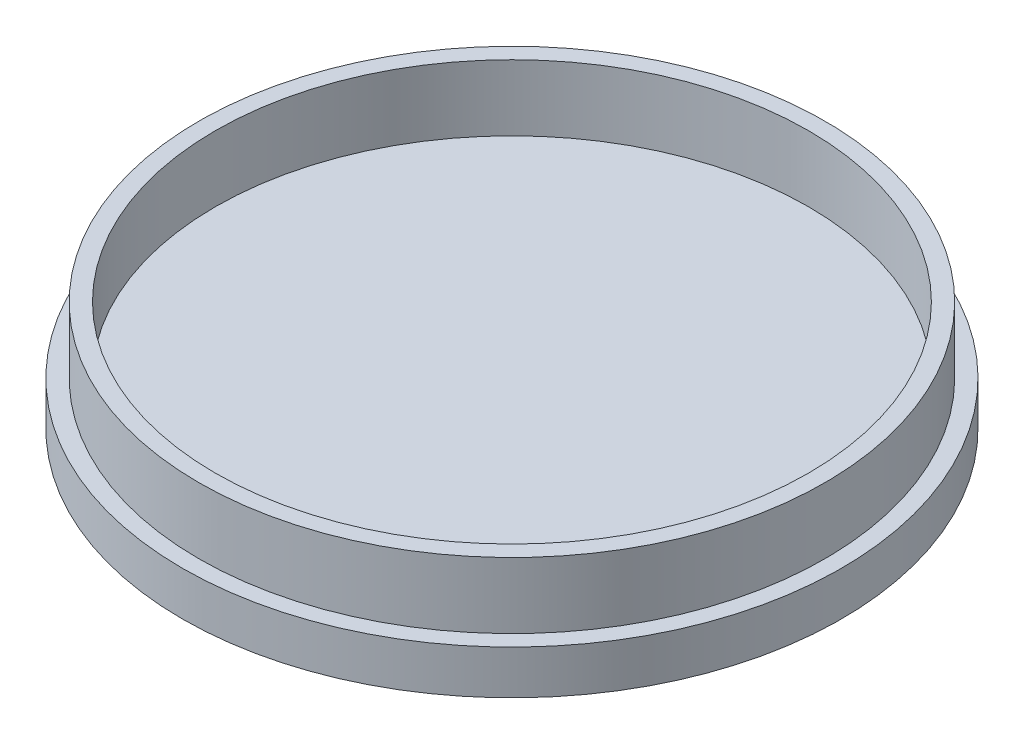
SolidWorks part; units mm, degrees
material "6061-T6 (SS)"
ref_plane "Front Plane" through (0, 0, 0) normal (0, 0, 1) x (1, 0, 0)
ref_plane "Top Plane" through (0, 0, 0) normal (0, 1, 0) x (1, 0, 0)
ref_plane "Right Plane" through (0, 0, 0) normal (1, 0, 0) x (0, 0, -1)
sketch "Sketch1" plane through (0, 0, 0) normal (0, 1, 0) x (1, 0, 0)
  circle A3 centre (0, 0) radius 15
  dimension "D1" = 30
extrude "Boss-Extrude3" add sketch "Sketch1" along normal blind 2
sketch "Sketch2" plane through (0, 2, 0) normal (0, 1, 0) x (1, 0, 0)
  circle A0 centre (0, 0) radius 13.5
  circle A1 centre (0, 0) radius 14.25
  dimension "D1" = 28.5
  dimension "D2" = 27
extrude "Boss-Extrude4" add sketch "Sketch2" along normal blind 3
sketch "Sketch6" plane through (0, 0, 0) normal (0, -1, 0) x (1, 0, 0)
  circle A0 centre (0, 3.5) radius 0.5
  dimension "D1" = 1
  dimension "D2" = 3.5
sketch "Sketch7" plane through (0, 0, 0) normal (1, 0, 0) x (0, 0, -1)
  line L0 (-3.5, 0) -> (-3.5, -1)
  line L1 (-4, 0) -> (-3, 0) construction
  line L2 (-2.5, -2) -> (2.5, -2)
  line L3 (3.5, -1) -> (3.5, 0)
  line L4 (-15, 0) -> (15, 0) construction
  line L5 (0, 0) -> (0, -3.4277) construction
  arc A0 (2.5, -2) -> (3.5, -1) centre (2.5, -1) ccw
  arc A1 (-2.5, -2) -> (-3.5, -1) centre (-2.5, -1) cw
  point P15 (-3.5, -2)
  dimension "D2" = 1
  dimension "D1" = 2
sweep "Sweep1" add profiles "Sketch6" path "Sketch7"
